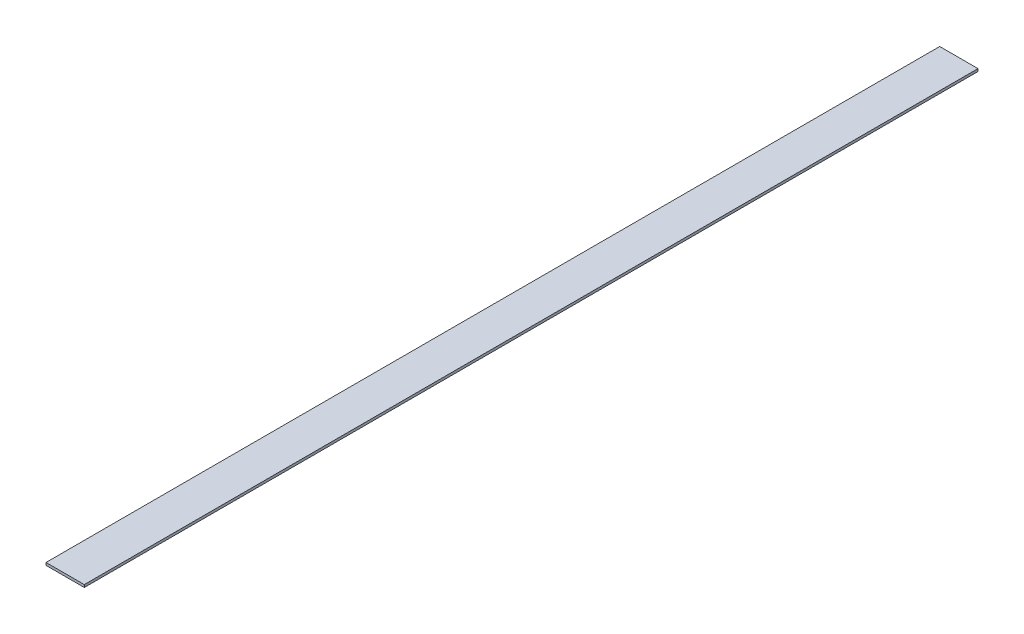
SolidWorks part; units mm, degrees
ref_plane "Front Plane" through (0, 0, 0) normal (0, 0, 1) x (1, 0, 0)
ref_plane "Top Plane" through (0, 0, 0) normal (0, 1, 0) x (1, 0, 0)
ref_plane "Right Plane" through (0, 0, 0) normal (1, 0, 0) x (0, 0, -1)
sketch "Sketch1" plane through (0, 0, 0) normal (0, 0, 1) x (1, 0, 0)
  line L1 (-7.5, 0.5) -> (7.5, 0.5)
  line L2 (-7.5, 0.5) -> (-7.5, -0.5)
  line L3 (-7.5, -0.5) -> (7.5, -0.5)
  line L4 (7.5, 0.5) -> (7.5, -0.5)
  line L5 (-7.5, 0.5) -> (7.5, -0.5) construction
  line L6 (-7.5, -0.5) -> (7.5, 0.5) construction
  point P0 (0, 0)
  dimension "D1" = 1
  dimension "D2" = 15
extrude "Boss-Extrude1" add sketch "Sketch1" along normal blind 350
